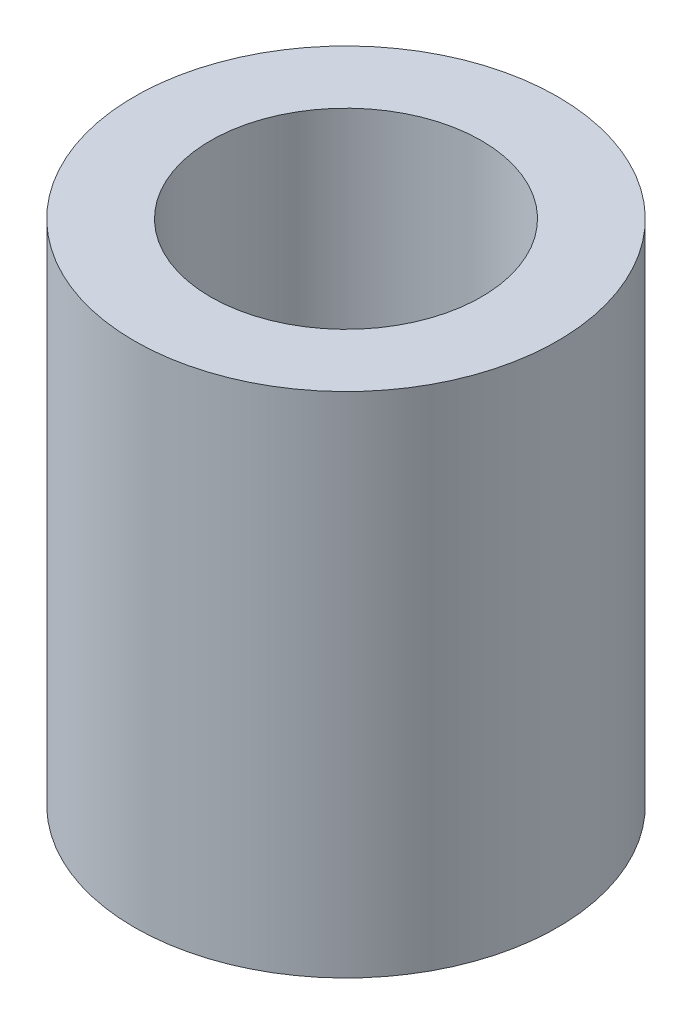
SolidWorks part; units mm, degrees
ref_plane "Plano frontal" through (0, 0, 0) normal (0, 0, 1) x (1, 0, 0)
ref_plane "Plano superior" through (0, 0, 0) normal (0, 1, 0) x (1, 0, 0)
ref_plane "Plano direito" through (0, 0, 0) normal (1, 0, 0) x (0, 0, -1)
sketch "Esboço1" plane through (0, 0, 0) normal (0, 1, 0) x (1, 0, 0)
  circle A0 centre (0, 0) radius 12.5
  dimension "D1" = 25
extrude "Ressalto-extrusão1" add sketch "Esboço1" along normal blind 30
sketch "Esboço2" plane through (0, 30, 0) normal (0, 1, 0) x (1, 0, 0)
  circle A0 centre (0, 0) radius 8
extrude "Corte-extrusão1" cut sketch "Esboço2" against normal blind 15
sketch "Esboço3" plane through (0, 0, 0) normal (0, -1, 0) x (1, 0, 0)
  line L1 (-1.5, 2.5) -> (1.5, 2.5)
  line L2 (-1.5, 2.5) -> (-1.5, -2.5)
  line L3 (-1.5, -2.5) -> (1.5, -2.5)
  line L4 (1.5, 2.5) -> (1.5, -2.5)
  circle A0 centre (0, 0) radius 12.5 construction
  dimension "D1" = 3
  dimension "D2" = 5
  dimension "D3" = 1.5
  dimension "D4" = 2.5
extrude "Corte-extrusão2" cut sketch "Esboço3" against normal blind 6.5
